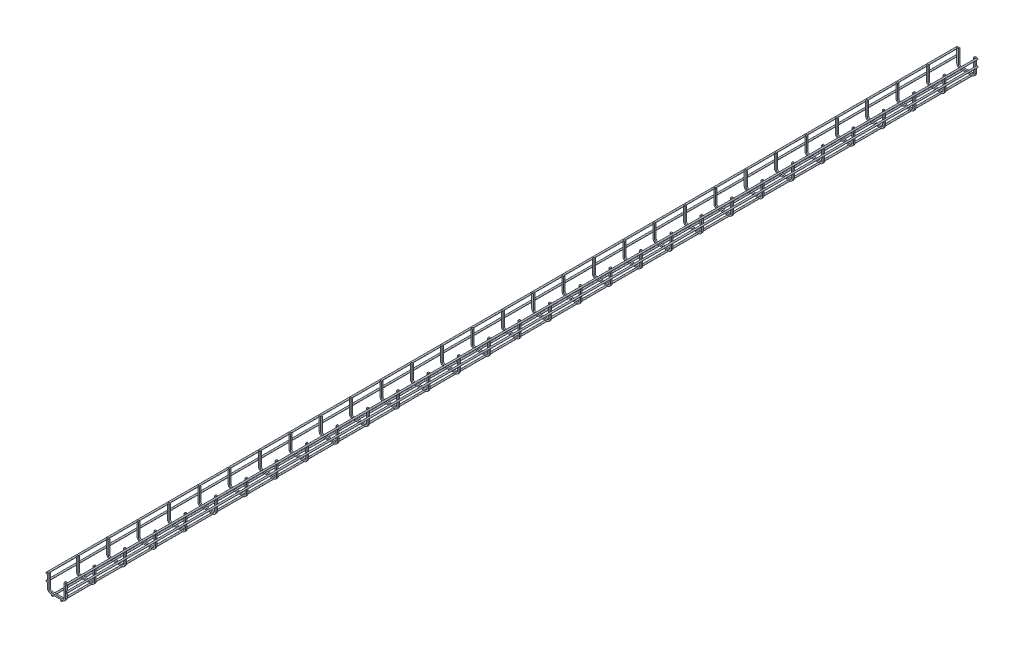
SolidWorks part; units mm, degrees
material "V2a"
ref_plane "Ebene1" through (0, 0, 0) normal (0, 0, 1) x (1, 0, 0)
ref_plane "Ebene2" through (0, 0, 0) normal (0, 1, 0) x (1, 0, 0)
ref_plane "Ebene3" through (0, 0, 0) normal (1, 0, 0) x (0, 0, -1)
sketch "Skizze1" plane through (0, 0, 0) normal (0, 0, 1) x (1, 0, 0)
  line L0 (0, 0) -> (0, 80.0472) construction
  line L1 (-30, 59.999) -> (-30, 57.5697)
  line L2 (-14.9293, 0) -> (14.9293, 0) construction
  line L3 (-14.8586, 4.999) -> (14.8586, 4.999)
  line L4 (30, 59.999) -> (30, 57.5697)
  line L5 (-20, 9.999) -> (20, 9.999)
  line L6 (25, 59.999) -> (25, 14.999)
  line L7 (-34.999, 34.999) -> (34.999, 34.999) construction
  line L8 (25, 59.999) -> (30, 59.999)
  line L9 (30, 57.4283) -> (30, 35.0697)
  line L10 (30, 59.999) -> (30, 14.999) construction
  line L11 (30, 34.9283) -> (30, 14.999)
  line L12 (15, 4.999) -> (20, 4.999)
  line L13 (-26.7724, 4.999) -> (20, 4.999) construction
  line L14 (-60, 60) -> (-60, 20) construction
  line L15 (-55, 60) -> (-55, 20) construction
  line L16 (-28.8206, 9.999) -> (20, 9.999) construction
  line L17 (-15, 4.999) -> (-20, 4.999)
  line L18 (-30, 34.9283) -> (-30, 14.999)
  line L19 (-30, 57.4283) -> (-30, 35.0697)
  line L20 (-25, 59.999) -> (-30, 59.999)
  line L21 (-25, 59.999) -> (-25, 14.999)
  arc A0 (20, 4.999) -> (30, 14.999) centre (20, 14.999) ccw
  arc A1 (-14.8586, 4.999) -> (-15, 4.999) centre (-14.9293, 2.5) cw
  arc A2 (-30, 34.9283) -> (-30, 35.0697) centre (-32.499, 34.999) cw
  arc A3 (20, 9.999) -> (25, 14.999) centre (20, 14.999) ccw
  arc A4 (30, 57.4283) -> (30, 57.5697) centre (32.499, 57.499) ccw
  arc A5 (30, 34.9283) -> (30, 35.0697) centre (32.499, 34.999) ccw
  arc A6 (14.8586, 4.999) -> (15, 4.999) centre (14.9293, 2.5) ccw
  arc A7 (-55, 20) -> (-28.8206, 9.999) centre (-40, 20) ccw construction
  arc A8 (-60, 20) -> (-26.7724, 4.999) centre (-40, 20) ccw construction
  arc A9 (-30, 57.4283) -> (-30, 57.5697) centre (-32.499, 57.499) cw
  arc A10 (-20, 9.999) -> (-25, 14.999) centre (-20, 14.999) cw
  arc A11 (-20, 4.999) -> (-30, 14.999) centre (-20, 14.999) cw
  point P45 (0, 9.999)
  dimension "D1" = 10
  dimension "D3" = 5
  dimension "D4" = 50
  dimension "D5" = 5
  dimension "D7" = 2.5
  dimension "D9" = 50
  dimension "D2" = 5
  dimension "D6" = 2.499
  dimension "D8" = 2.499
extrude "Basis-Linear austragen" add sketch "Skizze1" against normal mid plane 3000
sketch "Skizze2" plane through (0, 0, -1500) normal (0, 0, 1) x (1, 0, 0)
  line L0 (30, 59.999) -> (25, 59.999) construction
  line L1 (25, 59.999) -> (25, 14.999) construction
  line L2 (20, 9.999) -> (-20, 9.999) construction
  line L3 (-25, 14.999) -> (-25, 59.999) construction
  line L4 (-25, 59.999) -> (-30, 59.999) construction
  line L5 (30, 59.999) -> (25, 59.999)
  line L6 (25, 59.999) -> (25, 14.999)
  line L7 (20, 9.999) -> (-20, 9.999)
  line L8 (-25, 14.999) -> (-25, 59.999)
  line L9 (-25, 59.999) -> (-30, 59.999)
  line L10 (30, 59.999) -> (30, 14.999)
  line L11 (20, 4.999) -> (-20, 4.999)
  line L12 (-30, 14.999) -> (-30, 59.999)
  arc A0 (20, 4.999) -> (30, 14.999) centre (20, 14.999) ccw construction
  arc A1 (20, 9.999) -> (25, 14.999) centre (20, 14.999) ccw construction
  arc A2 (-30, 14.999) -> (-20, 4.999) centre (-20, 14.999) ccw construction
  arc A3 (-25, 14.999) -> (-20, 9.999) centre (-20, 14.999) ccw construction
  arc A4 (20, 4.999) -> (30, 14.999) centre (20, 14.999) ccw
  arc A5 (20, 9.999) -> (25, 14.999) centre (20, 14.999) ccw
  arc A6 (-30, 14.999) -> (-20, 4.999) centre (-20, 14.999) ccw
  arc A7 (-25, 14.999) -> (-20, 9.999) centre (-20, 14.999) ccw
extrude "Schnitt-Linear austragen1" cut sketch "Skizze2" along normal blind 95 from offset 5
pattern_linear "Lineares Muster1" count 30 spacing 100 along (0, 0, 1) of "Schnitt-Linear austragen1"
sketch "Skizze3" plane through (0, 0, 1500) normal (0, 0, 1) x (1, 0, 0)
  line L18 (30, 14.999) -> (30, 34.9283)
  line L19 (30, 34.9283) -> (30, 35.0697)
  line L20 (30, 35.0697) -> (30, 57.4283)
  line L21 (30, 57.4283) -> (30, 57.5697)
  line L22 (30, 57.5697) -> (30, 59.999)
  line L23 (30, 59.999) -> (25, 59.999)
  line L24 (25, 59.999) -> (25, 14.999)
  line L25 (20, 9.999) -> (-20, 9.999)
  line L26 (-25, 14.999) -> (-25, 59.999)
  line L27 (-25, 59.999) -> (-30, 59.999)
  line L28 (-30, 59.999) -> (-30, 57.5697)
  line L29 (-30, 57.5697) -> (-30, 57.4283)
  line L30 (-30, 57.4283) -> (-30, 35.0697)
  line L31 (-30, 35.0697) -> (-30, 34.9283)
  line L32 (-30, 34.9283) -> (-30, 14.999)
  line L33 (-20, 4.999) -> (-15, 4.999)
  line L34 (-14.8586, 4.999) -> (14.8586, 4.999)
  line L35 (-20, 4.999) -> (-15, 4.999)
  line L36 (30, 14.999) -> (30, 34.9283)
  line L37 (30, 34.9283) -> (30, 35.0697)
  line L38 (30, 35.0697) -> (30, 57.4283)
  line L39 (30, 57.4283) -> (30, 57.5697)
  line L40 (30, 57.5697) -> (30, 59.999)
  line L41 (30, 59.999) -> (25, 59.999)
  line L42 (25, 59.999) -> (25, 14.999)
  line L43 (20, 9.999) -> (-20, 9.999)
  line L44 (-25, 14.999) -> (-25, 59.999)
  line L45 (-25, 59.999) -> (-30, 59.999)
  line L46 (-30, 59.999) -> (-30, 57.5697)
  line L47 (-30, 57.5697) -> (-30, 57.4283)
  line L48 (-30, 57.4283) -> (-30, 35.0697)
  line L49 (-30, 35.0697) -> (-30, 34.9283)
  line L50 (-30, 34.9283) -> (-30, 14.999)
  line L51 (-15, 4.999) -> (-14.8586, 4.999)
  line L52 (-14.8586, 4.999) -> (14.8586, 4.999)
  line L53 (-15, 4.999) -> (-14.8586, 4.999)
  line L56 (14.8586, 4.999) -> (15, 4.999)
  line L57 (14.8586, 4.999) -> (15, 4.999)
  line L58 (15, 4.999) -> (20, 4.999)
  line L59 (15, 4.999) -> (20, 4.999)
  arc A4 (20, 4.999) -> (30, 14.999) centre (20, 14.999) ccw
  arc A5 (20, 9.999) -> (25, 14.999) centre (20, 14.999) ccw
  arc A6 (-25, 14.999) -> (-20, 9.999) centre (-20, 14.999) ccw
  arc A7 (-30, 14.999) -> (-20, 4.999) centre (-20, 14.999) ccw
  arc A8 (20, 4.999) -> (30, 14.999) centre (20, 14.999) ccw
  arc A9 (20, 9.999) -> (25, 14.999) centre (20, 14.999) ccw
  arc A10 (-25, 14.999) -> (-20, 9.999) centre (-20, 14.999) ccw
  arc A11 (-30, 14.999) -> (-20, 4.999) centre (-20, 14.999) ccw
  dimension "D1" = 0
extrude "Aufsatz-Linear austragen1" add sketch "Skizze3" against normal blind 5
sketch "Skizze4" [suppressed] plane through (0, 0, 0) normal (1, 0, 0) x (0, 0, -1)
  line L0 (1500, 20.0707) -> (1500, 47.4293) construction
  line L1 (1500, 50) -> (500, 50)
  line L2 (1500, 50) -> (1500, -4.999)
  line L3 (1500, -4.999) -> (500, -4.999)
  line L4 (500, 50) -> (500, -4.999)
  line L5 (1500, 50) -> (1495, 50) construction
  line L6 (-1500, -4.999) -> (1500, -4.999) construction
  line L7 (-1500, 20.0707) -> (-1500, 47.4293) construction
  dimension "D1" = 2000
extrude "Schnitt-Linear austragen2" [suppressed] cut sketch "Skizze4" against normal through all both and the other way through all
